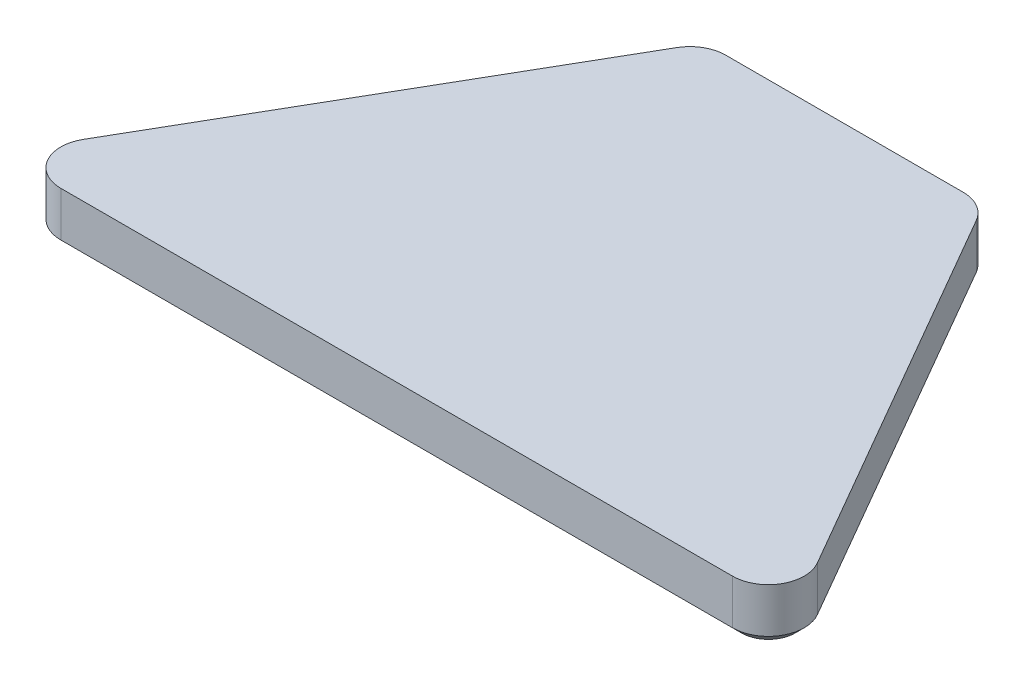
SolidWorks part; units mm, degrees
material "99.5% Aluminum Oxide"
ref_plane "Front Plane" through (0, 0, 0) normal (0, 0, 1) x (1, 0, 0)
ref_plane "Top Plane" through (0, 0, 0) normal (0, 1, 0) x (1, 0, 0)
ref_plane "Right Plane" through (0, 0, 0) normal (1, 0, 0) x (0, 0, -1)
sketch "Sketch1" plane through (0, 0, 0) normal (0, 1, 0) x (1, 0, 0)
  line L1 (-14.2978, -12.5) -> (14.2978, -12.5)
  line L2 (-14.2978, -12.5) -> (-14.2978, 12.5) construction
  line L3 (-14.2978, 12.5) -> (14.2978, 12.5) construction
  line L4 (14.2978, -12.5) -> (14.2978, 12.5) construction
  line L5 (-14.2978, -12.5) -> (14.2978, 12.5) construction
  line L6 (-14.2978, 12.5) -> (14.2978, -12.5) construction
  line L8 (-7.7831, 12.5) -> (7.7831, 12.5)
  line L11 (0, 11.2271) -> (0, -49988.7729) construction
  line L14 (-7.7831, 12.5) -> (-22.2169, -12.5)
  line L15 (-22.2169, -12.5) -> (-14.2978, -12.5)
  line L16 (7.7831, 12.5) -> (22.2169, -12.5)
  line L17 (22.2169, -12.5) -> (14.2978, -12.5)
  line L24 (15, 0) -> (-15, 0) construction
  point P0 (0, 0)
  point P14 (0, 12.5)
  dimension "D1" = 25
  dimension "D2" = 30
  dimension "D4" = 60
extrude "Boss-Extrude1" add sketch "Sketch1" along normal mid plane 3
fillet "Fillet5" radius 2 4 edges at (22.2169, 0, 12.5) (-22.2169, 0, 12.5) (-7.7831, 0, -12.5) (7.7831, 0, -12.5)
chamfer "Chamfer1" distance 0.5 angle 45 8 edges at (-20.4848, -1.5, 11.5) (0, -1.5, 12.5) (20.4848, -1.5, 11.5) (14.4226, -1.5, -1) (7.6284, -1.5, -12.2321) (0, -1.5, -12.5) (-7.6284, -1.5, -12.2321) (-14.4226, -1.5, -1)
equation "\"panel_width\"= 5.5in"
equation "\"finger_joint_width\"= 30mm"
